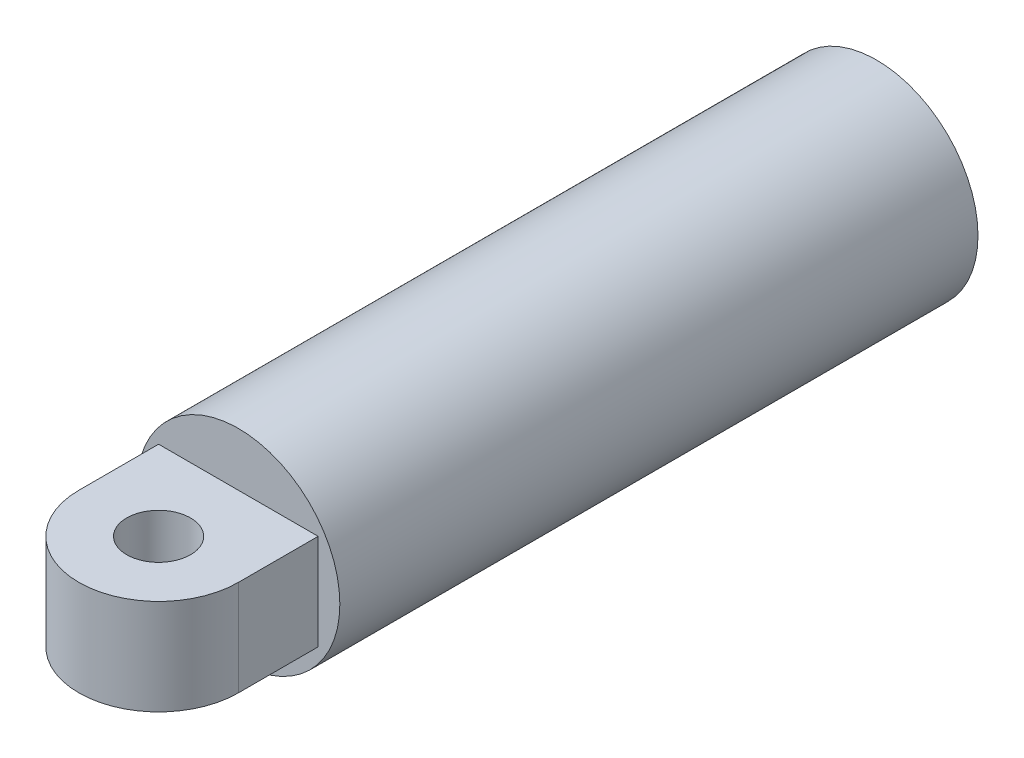
SolidWorks part; units mm, degrees
material "6061 Сплав"
ref_plane "Спереди" through (0, 0, 0) normal (0, 0, 1) x (1, 0, 0)
ref_plane "Сверху" through (0, 0, 0) normal (0, 1, 0) x (1, 0, 0)
ref_plane "Справа" through (0, 0, 0) normal (1, 0, 0) x (0, 0, -1)
sketch "Эскиз1" plane through (0, 0, 0) normal (0, 0, 1) x (1, 0, 0)
  circle A0 centre (0, 0) radius 15.9
  dimension "D1" = 31.8
extrude "Бобышка-Вытянуть1" add sketch "Эскиз1" along normal blind 100
sketch "Эскиз2" plane through (0, 0, 100) normal (0, 0, 1) x (1, 0, 0)
  line L1 (-12.5, 7.5) -> (12.5, 7.5)
  line L2 (-12.5, 7.5) -> (-12.5, -7.5)
  line L3 (-12.5, -7.5) -> (12.5, -7.5)
  line L4 (12.5, 7.5) -> (12.5, -7.5)
  line L5 (0, -7.5) -> (0, 7.5) construction
  line L6 (-12.5, 0) -> (12.5, 0) construction
  point P0 (0, 0)
extrude "Бобышка-Вытянуть2" add sketch "Эскиз2" along normal blind 25
sketch "Эскиз3" plane through (0, -7.5, 0) normal (0, 1, 0) x (1, 0, 0)
  line L2 (-12.5, -112.5) -> (-20.6999, -112.5)
  line L3 (-20.6999, -112.5) -> (-20.6999, -150.9737)
  line L4 (-20.6999, -150.9737) -> (17.8415, -150.9737)
  line L5 (17.8415, -150.9737) -> (17.8415, -132.5)
  line L6 (17.8415, -132.5) -> (12.5, -112.5)
  line L7 (12.5, -125) -> (12.5, -100) construction
  line L8 (-12.5, -125) -> (-12.5, -100) construction
  circle A0 centre (0, -112.5) radius 5
  arc A1 (-12.5, -112.5) -> (12.5, -112.5) centre (0, -112.5) ccw
extrude "Вырез-Вытянуть1" cut sketch "Эскиз3" along normal through all
sketch "Эскиз4" plane through (0, 0, 0) normal (0, 0, -1) x (-1, 0, 0)
  circle A0 centre (0, 0) radius 14
extrude "Вырез-Вытянуть2" cut sketch "Эскиз4" against normal blind 52
